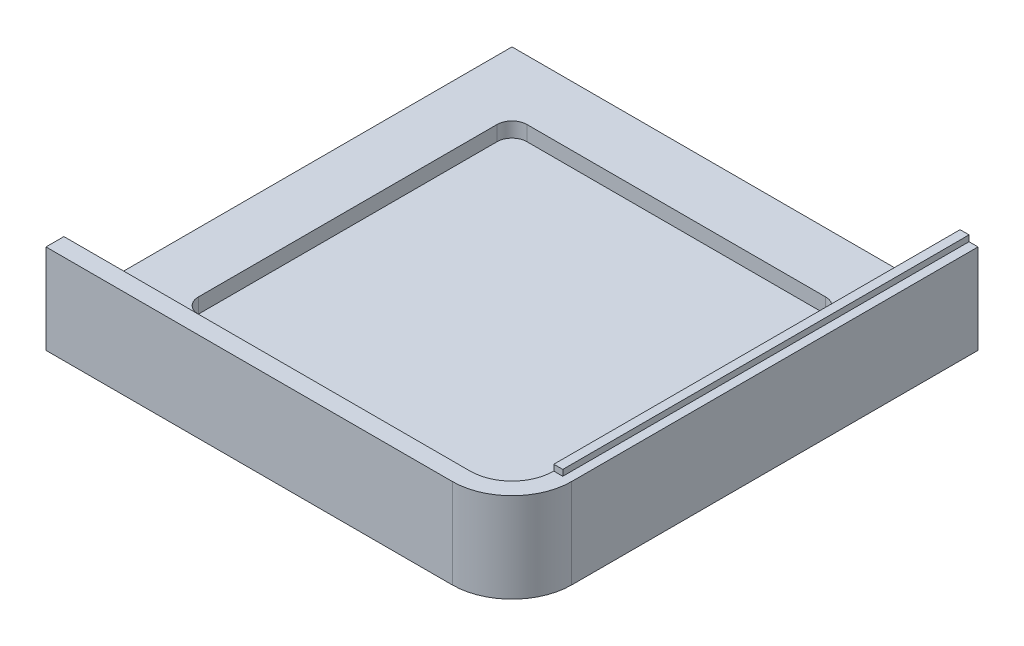
SolidWorks part; units mm, degrees
ref_plane "Ebene vorne" through (0, 0, 0) normal (0, 0, 1) x (1, 0, 0)
ref_plane "Ebene oben" through (0, 0, 0) normal (0, 1, 0) x (1, 0, 0)
ref_plane "Ebene rechts" through (0, 0, 0) normal (1, 0, 0) x (0, 0, -1)
sketch "Skizze9" plane through (0, 0, 0) normal (0, 1, 0) x (1, 0, 0)
  line L1 (0, 156) -> (156, 156)
  line L2 (0, 156) -> (0, 0)
  line L3 (0, 0) -> (156, 0)
  line L4 (156, 156) -> (156, 0)
  line L5 (20, 136) -> (130, 136)
  line L6 (20, 136) -> (20, 26)
  line L7 (20, 26) -> (130, 26)
  line L8 (130, 136) -> (130, 26)
  dimension "D1" = 20
  dimension "D2" = 20
  dimension "D3" = 26
  dimension "D4" = 26
  dimension "D5" = 110
extrude "Linear austragen4" add sketch "Skizze9" along normal blind 5
fillet "Verrundung5" radius 5 4 edges at (130, 2.5, -26) (20, 2.5, -26) (130, 2.5, -136) (20, 2.5, -136)
sketch "Skizze10" plane through (0, 0, 0) normal (0, -1, 0) x (1, 0, 0)
  line L1 (0, 0) -> (156, 0)
  line L2 (0, 0) -> (0, -156)
  line L3 (0, -156) -> (156, -156)
  line L4 (156, 0) -> (156, -156)
extrude "Linear austragen5" add sketch "Skizze10" along normal blind 5
sketch "Skizze11" plane through (0, 5, 0) normal (0, 1, 0) x (1, 0, 0)
  line L0 (0, 0) -> (156, 0)
  line L1 (156, 0) -> (156, 156)
  line L2 (156, 156) -> (150, 156)
  line L3 (156, 156) -> (0, 156) construction
  line L4 (150, 156) -> (150, 6)
  line L5 (150, 6) -> (0, 6)
  line L6 (0, 156) -> (0, 0) construction
  line L7 (0, 6) -> (0, 0)
  dimension "D1" = 6
extrude "Linear austragen6" add sketch "Skizze11" along normal blind 20
fillet "Verrundung6" radius 20 1 edges at (156, 10, 0)
fillet "Verrundung7" radius 14 1 edges at (150, 15, -6)
sketch "Skizze12" plane through (0, 25, 0) normal (0, 1, 0) x (1, 0, 0)
  line L0 (150, 156) -> (150, 20)
  line L1 (150, 20) -> (153, 20)
  line L2 (150, 156) -> (153, 156)
  line L4 (156, 156) -> (150, 156) construction
  line L7 (153, 156) -> (153, 20)
extrude "Linear austragen7" add sketch "Skizze12" along normal blind 2
